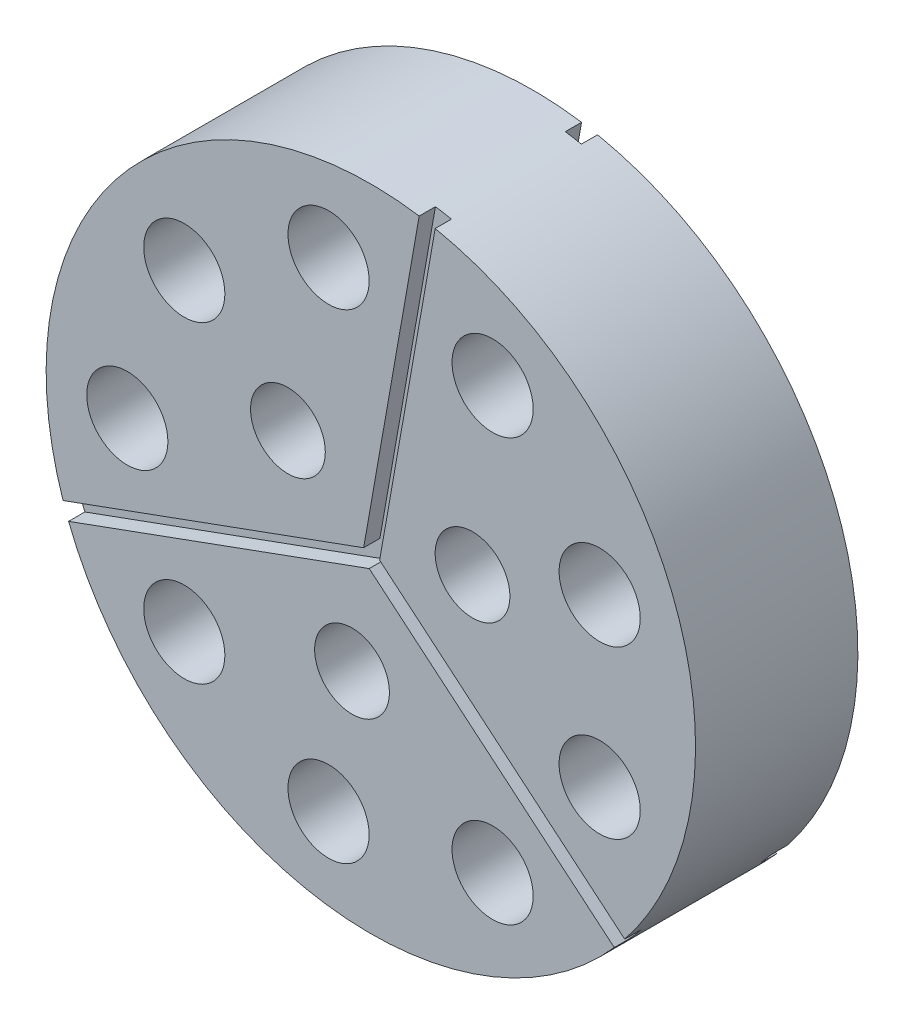
SolidWorks part; units mm, degrees
ref_plane "Front Plane" through (0, 0, 0) normal (0, 0, 1) x (1, 0, 0)
ref_plane "Top Plane" through (0, 0, 0) normal (0, 1, 0) x (1, 0, 0)
ref_plane "Right Plane" through (0, 0, 0) normal (1, 0, 0) x (0, 0, -1)
sketch "Sketch1" plane through (0, 0, 0) normal (0, 0, 1) x (1, 0, 0)
  circle A0 centre (0, 0) radius 20
  dimension "D1" = 40
extrude "Boss-Extrude1" add sketch "Sketch1" along normal blind 10
sketch "Sketch2" plane through (0, 0, 10) normal (0, 0, 1) x (1, 0, 0)
  line L0 (0, 0) -> (-20, 0) construction
  line L1 (0, 0) -> (15.3209, -12.8558) construction
  line L2 (0, 0) -> (3.473, 19.6962) construction
  line L3 (0, 0) -> (-18.7939, -6.8404) construction
  line L4 (0, 0) -> (-11.4907, 9.6418) construction
  circle A0 centre (-15, 0) radius 2.5
  circle A18 centre (0, 0) radius 20 construction
  circle A19 centre (-11.4907, 9.6418) radius 2.5
  circle A20 centre (-2.6047, 14.7721) radius 2.5
  circle A21 centre (7.5, 12.9904) radius 2.5
  circle A22 centre (14.0954, 5.1303) radius 2.5
  circle A23 centre (14.0954, -5.1303) radius 2.5
  circle A24 centre (7.5, -12.9904) radius 2.5
  circle A25 centre (-2.6047, -14.7721) radius 2.5
  circle A26 centre (-11.4907, -9.6418) radius 2.5
  circle A27 centre (-5.107, 4.2853) radius 2.3024
  circle A28 centre (6.2646, 2.2801) radius 2.3024
  circle A29 centre (-1.1577, -6.5654) radius 2.3024
  point P24 (0, 0)
  point P28 (0, 0)
  point P36 (0, 0)
  dimension "D2" = 5
  dimension "D1" = 15
  dimension "D3" = 6.6667
extrude "Cut-Extrude1" cut sketch "Sketch2" against normal blind 35
sketch "Sketch3" plane through (0, 0, 10) normal (0, 0, 1) x (1, 0, 0)
  line L0 (-2.6047, 14.7721) -> (7.5, 12.9904) construction
  line L1 (7.5, 12.9904) -> (3.473, 19.6962) construction
  line L2 (3.473, 19.6962) -> (-2.6047, 14.7721) construction
  line L3 (0, 0) -> (3.473, 19.6962) construction
  line L4 (0, 0) -> (15.3209, -12.8558) construction
  line L5 (0, 0) -> (-18.7939, -6.8404) construction
  line L6 (-18.617, -7.3081) -> (-0.1003, -0.5686)
  line L7 (-0.1003, -0.5686) -> (14.9947, -13.2348)
  line L8 (-18.959, -6.3684) -> (-0.4423, 0.3711)
  line L9 (-0.4423, 0.3711) -> (2.9795, 19.7768)
  line L10 (15.6375, -12.4687) -> (0.5425, 0.1975)
  line L11 (0.5425, 0.1975) -> (3.9643, 19.6032)
  circle A2 centre (0, 0) radius 20 construction
  arc A3 (-18.959, -6.3684) -> (-18.617, -7.3081) centre (0, 0) ccw
  arc A4 (14.9947, -13.2348) -> (15.6375, -12.4687) centre (0, 0) ccw
  arc A5 (2.9795, 19.7768) -> (3.9643, 19.6032) centre (0, 0) cw
  point P14 (0, 0)
  circle M18 centre (0, 0) radius 20
  dimension "D4" = 0.5
  dimension "D5" = 0.5
  dimension "D1" = 3
  dimension "D2" = 0.5
  dimension "D3" = 0.5
  dimension "D6" = 0.5
  dimension "D7" = 0.5
extrude "Cut-Extrude2" cut sketch "Sketch3" against normal blind 1 contours L10 L11 L9 L8 L6 L7 M18
ref_plane "Plane1" through (0, 0, 5) normal (0, 0, -1) x (-1, 0, 0)
mirror "Mirror1" about plane through (0, 0, 5) normal (0, 0, -1) of "Cut-Extrude2"
